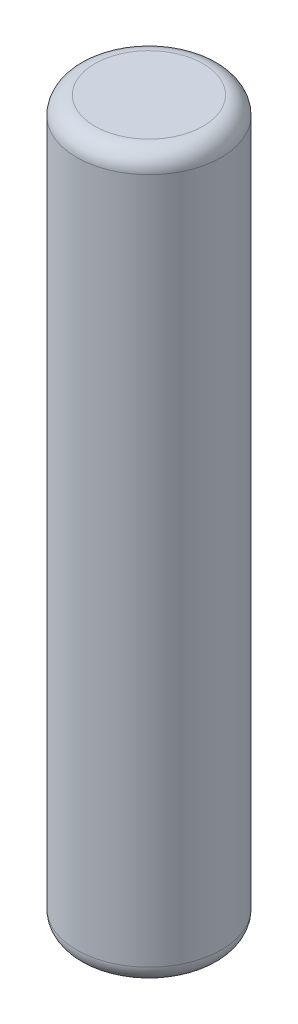
SolidWorks part; units mm, degrees
ref_plane "Front Plane" through (0, 0, 0) normal (0, 0, 1) x (1, 0, 0)
ref_plane "Top Plane" through (0, 0, 0) normal (0, 1, 0) x (1, 0, 0)
ref_plane "Right Plane" through (0, 0, 0) normal (1, 0, 0) x (0, 0, -1)
sketch "Sketch1" plane through (0, 0, 0) normal (0, 1, 0) x (1, 0, 0)
  circle A0 centre (0, 0) radius 4
  dimension "D1" = 8
extrude "Boss-Extrude1" add sketch "Sketch1" along normal blind 40
fillet "Fillet1" radius 1 2 edges at (0, 0, 4) (0, 40, 4)
scale "Scale1" scale about centroid uniform scaling yes scale factor 0.7
